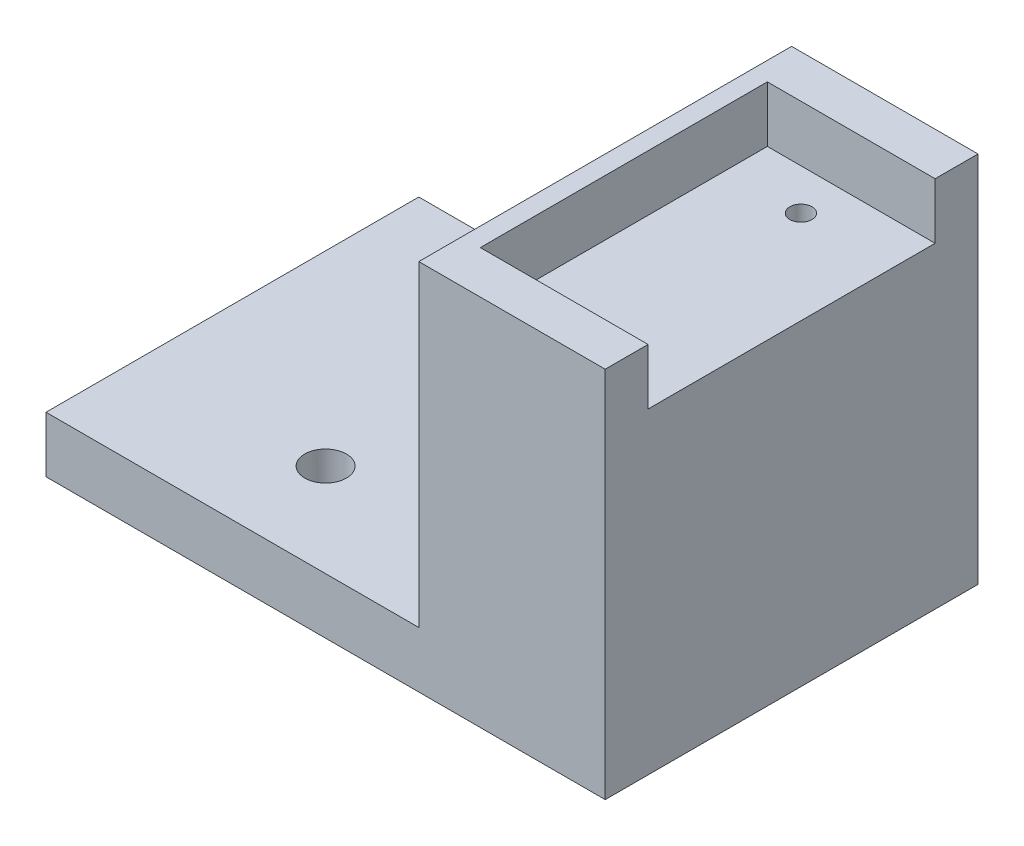
SolidWorks part; units mm, degrees
ref_plane "Front Plane" through (0, 0, 0) normal (0, 0, 1) x (1, 0, 0)
ref_plane "Top Plane" through (0, 0, 0) normal (0, 1, 0) x (1, 0, 0)
ref_plane "Right Plane" through (0, 0, 0) normal (1, 0, 0) x (0, 0, -1)
sketch "Sketch1" plane through (0, 0, 0) normal (1, 0, 0) x (0, 0, -1)
  line L1 (0, 0) -> (25.4, 0)
  line L2 (0, 0) -> (0, 25.4)
  line L3 (0, 25.4) -> (25.4, 25.4)
  line L4 (25.4, 0) -> (25.4, 25.4)
  dimension "D1" = 25.4
  dimension "D2" = 25.4
extrude "Boss-Extrude1" add sketch "Sketch1" along normal blind 12.7
sketch "Sketch2" plane through (0, 25.4, 0) normal (0, 1, 0) x (1, 0, 0)
  line L0 (12.7, 25.4) -> (12.7, 0) construction
  line L1 (12.7, 2.921) -> (1.27, 2.921)
  line L2 (12.7, 2.921) -> (12.7, 22.479)
  line L3 (12.7, 22.479) -> (1.27, 22.479)
  line L4 (1.27, 2.921) -> (1.27, 22.479)
  line L5 (12.7, 0) -> (0, 0) construction
  line L8 (12.7, 25.4) -> (0, 25.4) construction
  dimension "D1" = 19.558
  dimension "D2" = 2.921
  dimension "D3" = 2.921
  dimension "D4" = 11.43
extrude "Cut-Extrude1" cut sketch "Sketch2" against normal blind 3.81
sketch "Sketch3" plane through (0, 21.59, 0) normal (0, 1, 0) x (1, 0, 0)
  line L0 (12.7, 22.479) -> (1.27, 22.479) construction
  circle A0 centre (6.35, 19.685) radius 1.651
  circle A1 centre (6.35, 5.715) radius 1.651
  point P6 (6.35, 19.685)
  dimension "D1" = 3.302
  dimension "D2" = 3.302
  dimension "D3" = 5.08
  dimension "D4" = 2.794
  dimension "D5" = 13.97
shell "Shell2" thickness 5.08
hole_wizard "#1-64 Tapped Hole2" positions "Sketch6" profile "Sketch8" tap size "#1-64" standard "ANSI Inch"
sketch "Sketch6" plane through (0, 21.59, 0) normal (0, 1, 0) x (1, 0, 0)
  point P0 (6.35, 19.685)
  point P3 (6.35, 5.715)
sketch "Sketch8" plane through (6.35, 21.59, -19.685) normal (1, 0, 0) x (0, 0, 1)
  line L0 (0, 0) -> (0, 6.804)
  line L1 (0, 6.804) -> (0.7556, 6.35)
  line L2 (0.7556, 6.35) -> (0.7556, 0)
  line L5 (0.7556, 0) -> (0, 0)
  line L10 (0, 6.804) -> (-0.7557, 6.35) construction
  line L11 (0, -6.35) -> (0, 107.95) construction
  dimension "Tap Drill Dia." = 1.5113
  dimension "Tap Drill Depth" = 6.35
  dimension "Drill Angle" = 118
cosmetic thread "Hole Thread1" parameters "D1"=3.81, "D2"=1.8542
cosmetic thread "Hole Thread2" parameters "D1"=3.81, "D2"=1.8542
sketch "Sketch12" plane through (0, 0, 0) normal (0, -1, 0) x (1, 0, 0)
  line L1 (12.7, 0) -> (-25.4, 0)
  line L2 (12.7, 0) -> (12.7, -25.4)
  line L3 (12.7, -25.4) -> (-25.4, -25.4)
  line L4 (-25.4, 0) -> (-25.4, -25.4)
  dimension "D1" = 25.4
  dimension "D2" = 38.1
extrude "Boss-Extrude2" add sketch "Sketch12" against normal blind 3.81
sketch "Sketch13" plane through (0, 0, 0) normal (0, -1, 0) x (1, 0, 0)
  line L0 (-12.7, 0) -> (-12.7, -25.4) construction
  line L1 (12.7, 0) -> (-25.4, 0) construction
  line L2 (12.7, -25.4) -> (-25.4, -25.4) construction
  line L3 (-25.4, 0) -> (-25.4, -25.4) construction
  point P8 (-12.7, -6.35)
  point P9 (-12.7, -19.05)
  dimension "D1" = 12.7
  dimension "D2" = 6.35
  dimension "D3" = 6.35
sketch "Sketch15" plane through (0, 0, 0) normal (0, -1, 0) x (1, 0, 0)
  line L0 (0, 0) -> (0, -25.4) construction
  line L1 (12.7, -25.4) -> (-25.4, -25.4) construction
  line L2 (6.35, 0) -> (6.35, -25.4) construction
  line L3 (12.7, 0) -> (-25.4, 0) construction
  line L5 (12.7, 0) -> (12.7, -25.4) construction
  line L6 (0, -12.7) -> (12.7, -12.7) construction
  dimension "D1" = 6.35
sketch "Sketch16" plane through (0, 0, 0) normal (0, -1, 0) x (1, 0, 0)
  circle A0 centre (-12.7, -6.35) radius 1.4224
  circle A1 centre (-12.7, -19.05) radius 1.4224
  dimension "D1" = 2.8448
extrude "Cut-Extrude2" cut sketch "Sketch16" against normal through all
